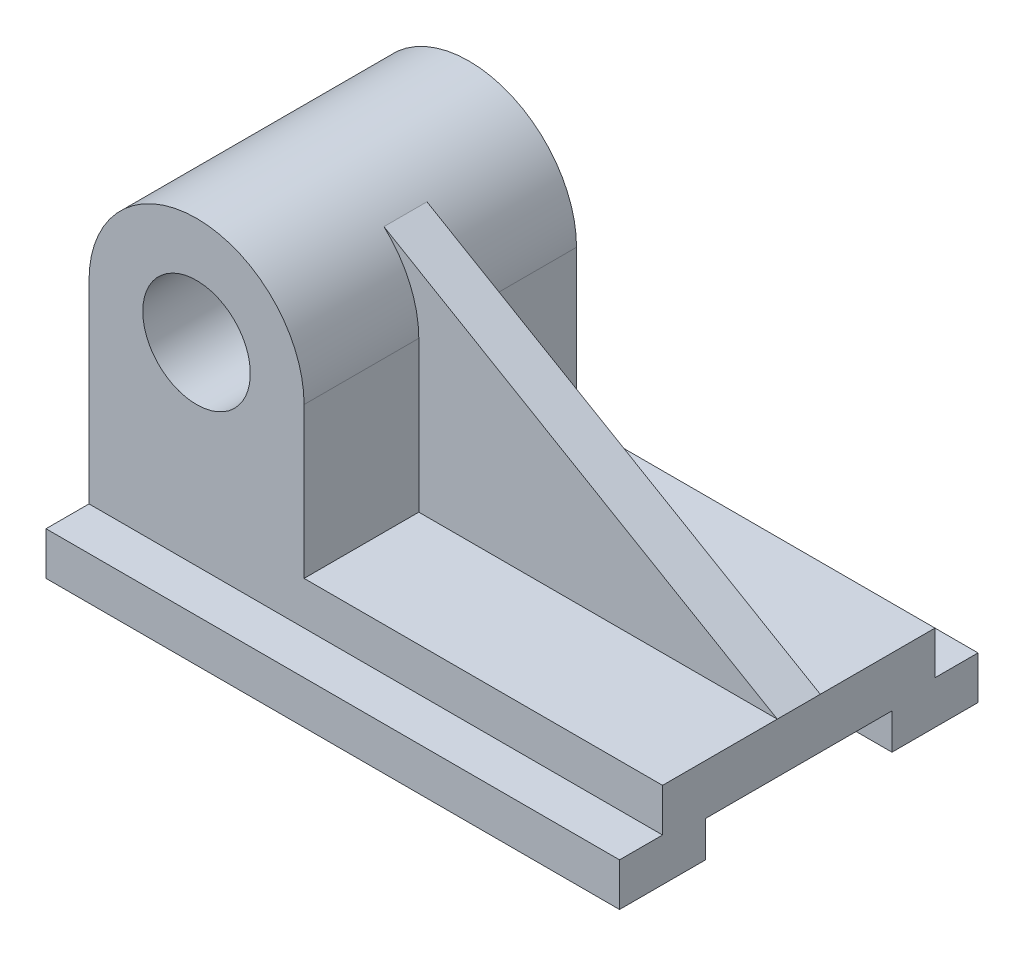
SolidWorks part; units mm, degrees
ref_plane "Front Plane" through (0, 0, 0) normal (0, 0, 1) x (1, 0, 0)
ref_plane "Top Plane" through (0, 0, 0) normal (0, 1, 0) x (1, 0, 0)
ref_plane "Right Plane" through (0, 0, 0) normal (1, 0, 0) x (0, 0, -1)
sketch "Sketch1" plane through (0, 0, 0) normal (0, 1, 0) x (1, 0, 0)
  line L1 (-80, 50) -> (80, 50)
  line L2 (-80, 50) -> (-80, -50)
  line L3 (-80, -50) -> (80, -50)
  line L4 (80, 50) -> (80, -50)
  line L5 (-80, 50) -> (80, -50) construction
  line L6 (-80, -50) -> (80, 50) construction
  point P0 (0, 0)
  dimension "D1" = 100
  dimension "D2" = 160
extrude "Boss-Extrude2" add sketch "Sketch1" along normal blind 24
sketch "Sketch3" plane through (80, 0, 0) normal (1, 0, 0) x (0, 0, -1)
  line L0 (-50, 0) -> (50, 0) construction
  line L1 (-26, 10) -> (26, 10)
  line L2 (-26, 10) -> (-26, 0)
  line L3 (-26, 0) -> (26, 0)
  line L4 (26, 10) -> (26, 0)
  line L5 (-26, 10) -> (26, 0) construction
  line L6 (-26, 0) -> (26, 10) construction
  line L7 (0, 35.0772) -> (0, -18.7191) construction
  point P0 (0, 5)
  dimension "D1" = 26
  dimension "D2" = 10
extrude "Cut-Extrude1" cut sketch "Sketch3" against normal blind 160
sketch "Sketch4" plane through (80, 0, 0) normal (1, 0, 0) x (0, 0, -1)
  line L1 (50, 24) -> (38, 24)
  line L2 (50, 24) -> (50, 12)
  line L3 (50, 12) -> (38, 12)
  line L4 (38, 24) -> (38, 12)
  dimension "D1" = 12
  dimension "D2" = 12
extrude "Cut-Extrude2" cut sketch "Sketch4" against normal blind 160
sketch "Sketch5" plane through (80, 0, 0) normal (1, 0, 0) x (0, 0, -1)
  line L1 (-50, 24) -> (-38, 24)
  line L2 (-50, 24) -> (-50, 12)
  line L3 (-50, 12) -> (-38, 12)
  line L4 (-38, 24) -> (-38, 12)
  dimension "D1" = 12
  dimension "D2" = 12
extrude "Cut-Extrude3" cut sketch "Sketch5" against normal blind 160
sketch "Sketch6" plane through (0, 0, -38) normal (0, 0, -1) x (-1, 0, 0)
  line L0 (80, 24) -> (80, 66)
  line L1 (80, 24) -> (80, 12) construction
  line L2 (20, 24) -> (20, 66)
  line L3 (80, 24) -> (-80, 24) construction
  line L4 (50, 106.4885) -> (50, -7.9052) construction
  line L5 (20, 24) -> (80, 24)
  arc A0 (80, 66) -> (20, 66) centre (50, 66) ccw
  circle A1 centre (50, 66) radius 15
  dimension "D3" = 30
  dimension "D4" = 30
  dimension "D1" = 42
  dimension "D2" = 42
extrude "Boss-Extrude3" add sketch "Sketch6" against normal blind 76
sketch "Sketch7" plane through (0, 0, 0) normal (0, 0, 1) x (1, 0, 0)
  line L0 (-20, 24) -> (80, 24)
  line L1 (80, 24) -> (-29.7284, 88.1147)
  line L2 (-20, 66) -> (-20, 24)
  arc A0 (-20, 66) -> (-80, 66) centre (-50, 66) ccw construction
  arc A1 (-20, 66) -> (-29.7284, 88.1147) centre (-50, 66) ccw
extrude "Boss-Extrude4" add sketch "Sketch7" along normal blind 6 and the other way blind 6
